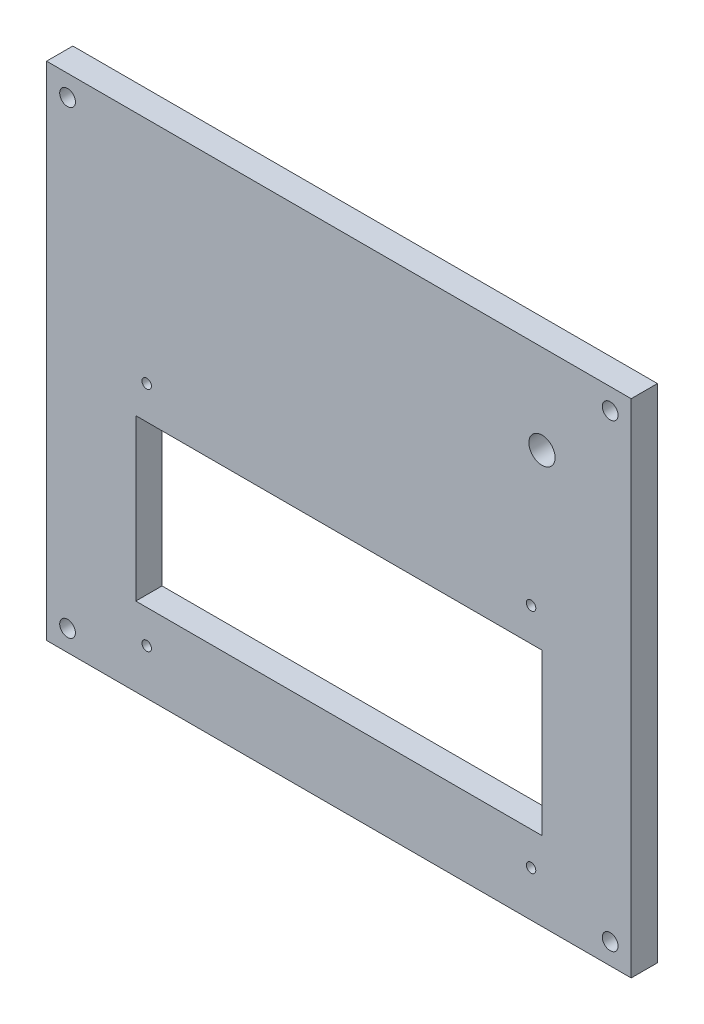
SolidWorks part; units mm, degrees
ref_plane "Front Plane" through (0, 0, 0) normal (0, 0, 1) x (1, 0, 0)
ref_plane "Top Plane" through (0, 0, 0) normal (0, 1, 0) x (1, 0, 0)
ref_plane "Right Plane" through (0, 0, 0) normal (1, 0, 0) x (0, 0, -1)
sketch "Sketch1" plane through (0, 0, 0) normal (0, 0, 1) x (1, 0, 0)
  line L1 (0, 0) -> (98.298, 0)
  line L2 (0, 0) -> (0, 38.862)
  line L3 (0, 38.862) -> (98.298, 38.862)
  line L4 (98.298, 0) -> (98.298, 38.862)
  line L5 (-21.59, 102.362) -> (119.888, 102.362)
  line L6 (-21.59, 102.362) -> (-21.59, -19.05)
  line L7 (-21.59, -19.05) -> (119.888, -19.05)
  line L8 (119.888, 102.362) -> (119.888, -19.05)
  circle A0 centre (98.298, 80.772) radius 3.175
  dimension "D7" = 6.35
  dimension "D8" = 21.59
  dimension "D9" = 21.59
  dimension "D1" = 98.298
  dimension "D2" = 38.862
  dimension "D3" = 21.59
  dimension "D4" = 21.59
  dimension "D5" = 63.5
  dimension "D6" = 19.05
  dimension "D10" = 141.478
  dimension "D11" = 121.412
extrude "Boss-Extrude1" add sketch "Sketch1" along normal blind 6.35
sketch "Sketch2" plane through (0, 0, 0) normal (0, 0, -1) x (-1, 0, 0)
  line L1 (0, 38.862) -> (-61.4736, 38.862)
  line L2 (0, 38.862) -> (0, 74.422)
  line L3 (0, 74.422) -> (-61.4736, 74.422)
  line L4 (-61.4736, 38.862) -> (-61.4736, 74.422)
  dimension "D1" = 35.56
  dimension "D2" = 61.4736
extrude "Cut-Extrude1" cut sketch "Sketch2" against normal blind 3.81
sketch "Sketch3" plane through (0, 0, 6.35) normal (0, 0, 1) x (1, 0, 0)
  line L0 (0, 38.862) -> (0, 0) construction
  line L5 (98.298, 0) -> (98.298, 38.862) construction
  line L6 (0.127, 49.4284) -> (0.127, -10.5664) construction
  line L7 (0.127, 49.4284) -> (98.171, 49.4284) construction
  line L8 (0.127, -10.5664) -> (98.171, -10.5664) construction
  line L9 (98.171, 49.4284) -> (98.171, -10.5664) construction
  line L10 (-21.59, -19.05) -> (119.888, -19.05) construction
  line L11 (-21.59, 102.362) -> (-21.59, -19.05) construction
  circle A0 centre (2.6416, 46.9138) radius 1.143
  circle A1 centre (95.6564, 46.9138) radius 1.143
  circle A2 centre (95.6564, -8.0518) radius 1.143
  circle A3 centre (2.6416, -8.0518) radius 1.143
  point P4 (0, 19.431)
  point P6 (0, 19.431)
  point P7 (98.298, 19.431)
  point P23 (1.4986, -8.0518)
  point P24 (2.6416, -9.1948)
  point P25 (2.6416, 45.7708)
  point P26 (1.4986, 46.9138)
  point P27 (2.6416, 48.0568)
  point P28 (95.6564, 48.0568)
  point P29 (96.7994, 46.9138)
  point P30 (96.7994, -8.0518)
  point P31 (95.6564, -9.1948)
  dimension "D7" = 2.286
  dimension "D8" = 2.286
  dimension "D9" = 2.286
  dimension "D10" = 2.286
  dimension "D11" = 1.3716
  dimension "D1" = 98.044
  dimension "D2" = 59.9948
  dimension "D3" = 59.9948
  dimension "D4" = 98.044
  dimension "D5" = 8.4836
  dimension "D6" = 21.717
  dimension "D12" = 1.3716
  dimension "D13" = 1.3716
  dimension "D14" = 1.3716
  dimension "D15" = 1.3716
  dimension "D16" = 1.3716
  dimension "D17" = 1.3716
  dimension "D18" = 1.3716
extrude "Cut-Extrude2" cut sketch "Sketch3" against normal through all
sketch "Sketch4" plane through (0, 0, 6.35) normal (0, 0, 1) x (1, 0, 0)
  line L0 (-21.59, 102.362) -> (-21.59, -19.05) construction
  line L1 (119.888, 102.362) -> (-21.59, 102.362) construction
  line L2 (-21.59, -19.05) -> (119.888, -19.05) construction
  line L3 (119.888, -19.05) -> (119.888, 102.362) construction
  circle A0 centre (-16.51, 97.282) radius 1.905
  circle A1 centre (-16.51, -13.97) radius 1.905
  circle A2 centre (114.808, -13.97) radius 1.905
  circle A3 centre (114.808, 97.282) radius 1.905
  dimension "D1" = 3.81
  dimension "D2" = 3.81
  dimension "D3" = 3.81
  dimension "D4" = 3.81
  dimension "D5" = 5.08
  dimension "D7" = 5.08
  dimension "D8" = 5.08
  dimension "D9" = 5.08
  dimension "D10" = 5.08
  dimension "D11" = 5.08
  dimension "D12" = 5.08
  dimension "D6" = 5.08
extrude "Cut-Extrude3" cut sketch "Sketch4" against normal through all
